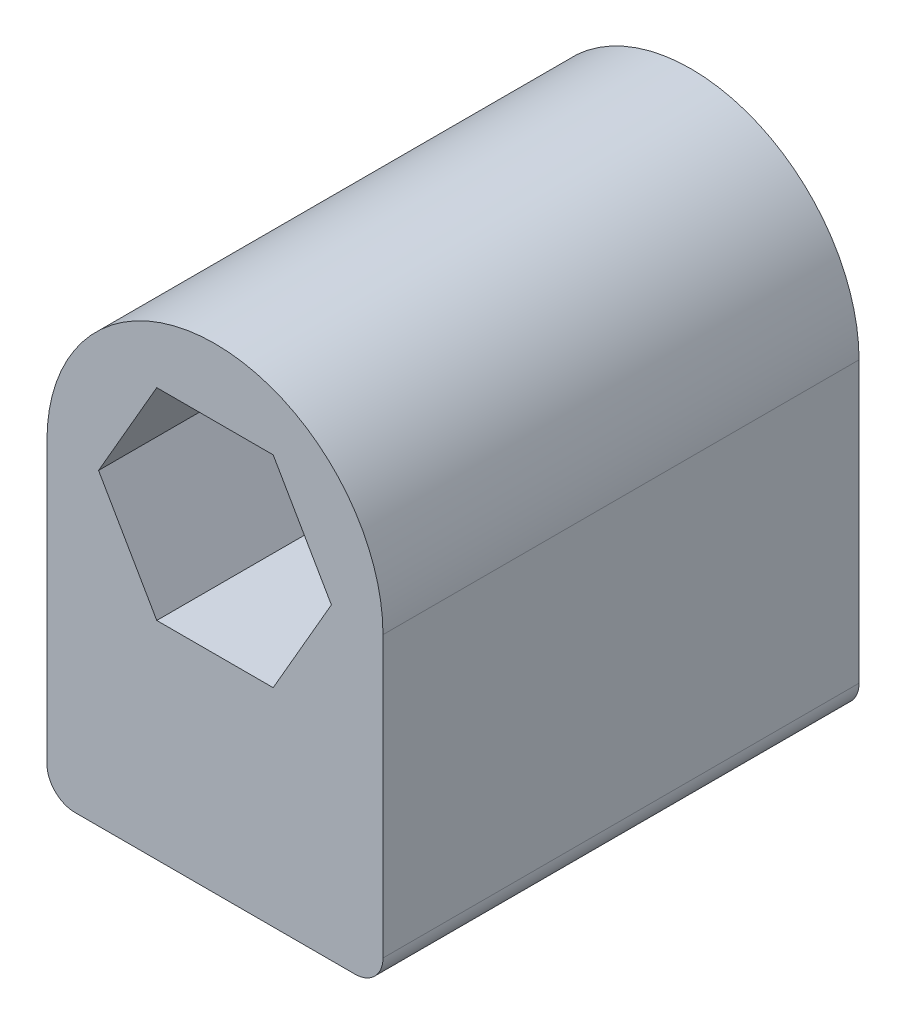
SolidWorks part; units mm, degrees
ref_plane "Front Plane" through (0, 0, 0) normal (0, 0, 1) x (1, 0, 0)
ref_plane "Top Plane" through (0, 0, 0) normal (0, 1, 0) x (1, 0, 0)
ref_plane "Right Plane" through (0, 0, 0) normal (1, 0, 0) x (0, 0, -1)
sketch "Sketch1" plane through (0, 0, 0) normal (0, 0, 1) x (1, 0, 0)
  line L1 (1, 0) -> (11, 0)
  line L2 (0, 1) -> (0, 11)
  line L4 (12, 1) -> (12, 11)
  line L5 (10.1569, 11) -> (8.0785, 14.6)
  line L6 (8.0785, 14.6) -> (3.9215, 14.6)
  line L7 (3.9215, 14.6) -> (1.8431, 11)
  line L8 (1.8431, 11) -> (3.9215, 7.4)
  line L9 (3.9215, 7.4) -> (8.0785, 7.4)
  line L10 (8.0785, 7.4) -> (10.1569, 11)
  arc A5 (12, 11) -> (0, 11) centre (6, 11) ccw
  arc A6 (11, 0) -> (12, 1) centre (11, 1) ccw
  arc A7 (1, 0) -> (0, 1) centre (1, 1) cw
extrude "Boss-Extrude1" add sketch "Sketch1" along normal blind 17
